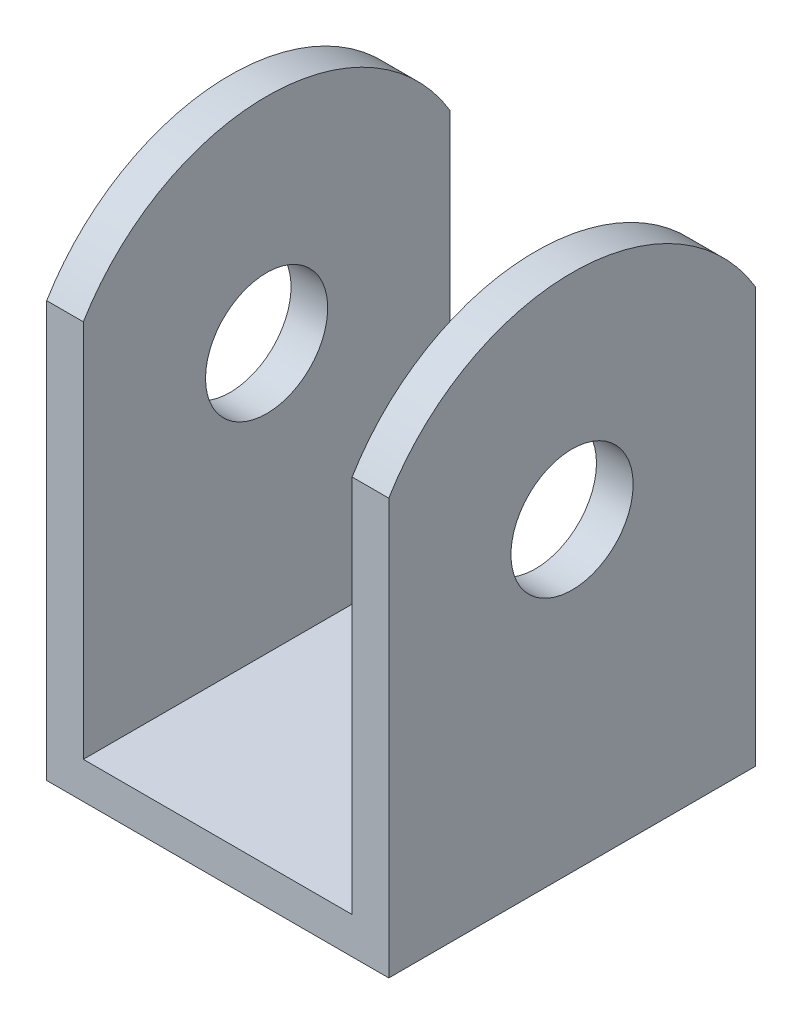
SolidWorks part; units mm, degrees
ref_plane "Front Plane" through (0, 0, 0) normal (0, 0, 1) x (1, 0, 0)
ref_plane "Top Plane" through (0, 0, 0) normal (0, 1, 0) x (1, 0, 0)
ref_plane "Right Plane" through (0, 0, 0) normal (1, 0, 0) x (0, 0, -1)
sketch "Sketch1" plane through (0, 0, 0) normal (0, 1, 0) x (1, 0, 0)
  line L1 (-56.186, 17.4186) -> (-34.186, 17.4186)
  line L2 (-56.186, 17.4186) -> (-56.186, -17.5814)
  line L3 (-56.186, -17.5814) -> (-34.186, -17.5814)
  line L4 (-34.186, 17.4186) -> (-34.186, -17.5814)
  dimension "D1" = 22
  dimension "D2" = 35
extrude "Boss-Extrude1" add sketch "Sketch1" along normal blind 3
sketch "Sketch2" plane through (-34.186, 0, 0) normal (1, 0, 0) x (0, 0, -1)
  line L1 (-17.5814, 0) -> (17.4186, 0)
  line L2 (-17.5814, 0) -> (-17.5814, 25)
  line L3 (-17.5814, 25) -> (17.4186, 25)
  line L4 (17.4186, 0) -> (17.4186, 25)
  circle A0 centre (-0.0814, 25) radius 17.5
  circle A1 centre (-0.0814, 25) radius 5
  line M3 (-17.5814, 0) -> (17.4186, 0)
  line M4 (17.4186, 0) -> (17.4186, 3)
  line M5 (17.4186, 3) -> (-17.5814, 3)
  line M6 (-17.5814, 3) -> (-17.5814, 0)
  dimension "D1" = 25
  dimension "D2" = 35
sketch "Sketch4" plane through (-56.186, 0, 0) normal (-1, 0, 0) x (0, 0, 1)
  line L1 (-17.4186, 0) -> (17.5814, 0)
  line L2 (-17.4186, 0) -> (-17.4186, 25)
  line L3 (-17.4186, 25) -> (17.5814, 25)
  line L4 (17.5814, 0) -> (17.5814, 25)
  circle A0 centre (0.0814, 25) radius 17.5
  circle A1 centre (0.0814, 25) radius 5
  line M3 (-17.4186, 0) -> (17.5814, 0)
  line M4 (17.5814, 0) -> (17.5814, 3)
  line M5 (17.5814, 3) -> (-17.4186, 3)
  line M6 (-17.4186, 3) -> (-17.4186, 0)
  dimension "D1" = 25
  dimension "D2" = 35
extrude "Boss-Extrude6" add sketch "Sketch2" along normal blind 3 contours A1 L3 A0 | A1 L3 A0 | A0 L2 L4 M5 | M6 M3 M4 M5
extrude "Boss-Extrude7" add sketch "Sketch4" along normal blind 3 contours A1 L3 A0 | A1 L3 A0 | A0 L2 L4 M5 | M6 M3 M4 M5
sketch "Sketch5" plane through (0, 0, 0) normal (0, -1, 0) x (1, 0, 0)
  line L0 (-31.186, 17.5814) -> (-31.186, -17.4186) construction
  line L1 (-59.186, 17.5814) -> (-31.186, 17.5814)
  line L2 (-59.186, 17.5814) -> (-59.186, 15.0814)
  line L3 (-59.186, 15.0814) -> (-31.186, 15.0814)
  line L4 (-31.186, 17.5814) -> (-31.186, 15.0814)
  line L6 (-59.186, -17.4186) -> (-31.186, -17.4186)
  line L7 (-59.186, -17.4186) -> (-59.186, -14.9186)
  line L8 (-59.186, -14.9186) -> (-31.186, -14.9186)
  line L9 (-31.186, -17.4186) -> (-31.186, -14.9186)
  dimension "D1" = 2.5
extrude "Cut-Extrude1" cut sketch "Sketch5" against normal blind 50
